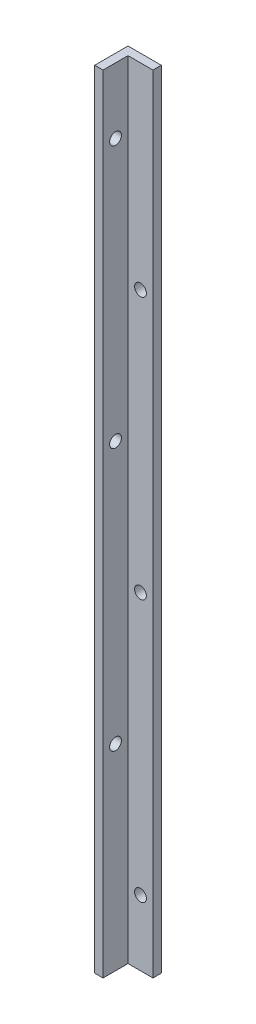
SolidWorks part; units mm, degrees
material "Alumina"
ref_plane "Front Plane" through (0, 0, 0) normal (0, 0, 1) x (1, 0, 0)
ref_plane "Top Plane" through (0, 0, 0) normal (0, 1, 0) x (1, 0, 0)
ref_plane "Right Plane" through (0, 0, 0) normal (1, 0, 0) x (0, 0, -1)
sketch "Sketch1" plane through (0, 0, 0) normal (0, 1, 0) x (1, 0, 0)
  line L0 (0, 0) -> (0, -12.7)
  line L1 (0, 0) -> (12.7, 0)
  line L2 (3.18, -3.18) -> (3.18, -12.7)
  line L3 (3.18, -3.18) -> (12.7, -3.18)
  line L4 (0, -12.7) -> (3.18, -12.7)
  line L5 (12.7, -3.18) -> (12.7, 0)
  dimension "D1" = 12.7
  dimension "D2" = 12.7
  dimension "D3" = 3.18
extrude "Boss-Extrude1" add sketch "Sketch1" along normal blind 300
sketch "Sketch2" plane through (3.18, 0, 0) normal (1, 0, 0) x (0, 0, -1)
  line L0 (-7.94, 300) -> (-7.94, 0) construction
  line L1 (-12.7, 300) -> (-3.18, 300) construction
  line L2 (-12.7, 0) -> (-3.18, 0) construction
  circle A0 centre (-7.94, 275) radius 2.25
  circle A1 centre (-7.94, 175) radius 2.25
  circle A2 centre (-7.94, 75) radius 2.25
  dimension "D2" = 4.5
  dimension "D1" = 25
extrude "Cut-Extrude1" cut sketch "Sketch2" against normal blind 10
sketch "Sketch3" plane through (0, 0, 3.18) normal (0, 0, 1) x (1, 0, 0)
  line L0 (7.94, 300) -> (7.94, 0) construction
  line L1 (3.18, 300) -> (12.7, 300) construction
  line L2 (3.18, 0) -> (12.7, 0) construction
  circle A0 centre (7.94, 225) radius 2.25
  circle A1 centre (7.94, 125) radius 2.25
  circle A2 centre (7.94, 25) radius 2.25
  dimension "D2" = 4.5
  dimension "D1" = 75
extrude "Cut-Extrude2" cut sketch "Sketch3" against normal blind 10
